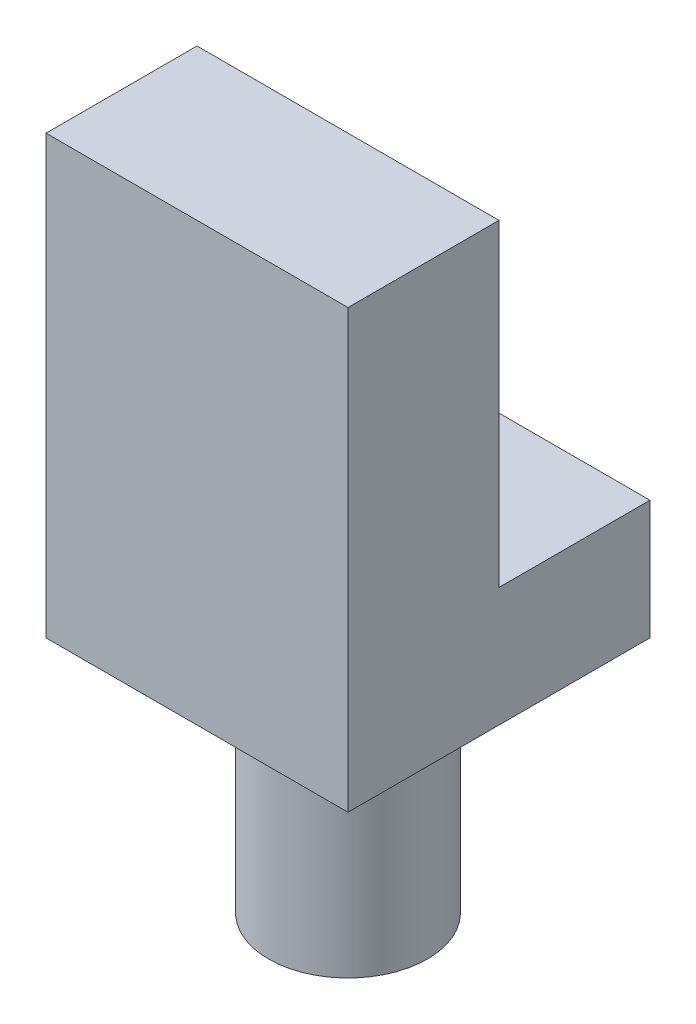
SolidWorks part; units mm, degrees
material "5086-H32, Rod (SS)"
ref_plane "Front Plane" through (0, 0, 0) normal (0, 0, 1) x (1, 0, 0)
ref_plane "Top Plane" through (0, 0, 0) normal (0, 1, 0) x (1, 0, 0)
ref_plane "Right Plane" through (0, 0, 0) normal (1, 0, 0) x (0, 0, -1)
sketch "Sketch1" plane through (0, 0, 0) normal (0, 1, 0) x (1, 0, 0)
  circle A0 centre (0, 0) radius 10
  dimension "D1" = 20
extrude "Boss-Extrude1" add sketch "Sketch1" along normal blind 30
sketch "Sketch2" plane through (0, 30, 0) normal (0, 1, 0) x (1, 0, 0)
  line L1 (-19, -19) -> (19, -19)
  line L2 (-19, -19) -> (-19, 19)
  line L3 (-19, 19) -> (19, 19)
  line L4 (19, -19) -> (19, 19)
  line L5 (-19, -19) -> (19, 19) construction
  line L6 (-19, 19) -> (19, -19) construction
  point P0 (0, 0)
  dimension "D1" = 38
extrude "Boss-Extrude2" add sketch "Sketch2" along normal blind 15
sketch "Sketch3" plane through (0, 45, 0) normal (0, 1, 0) x (1, 0, 0)
  line L0 (19, -19) -> (19, 19) construction
  line L1 (-19, -19) -> (19, -19)
  line L2 (-19, -19) -> (-19, 0)
  line L3 (-19, 0) -> (19, 0)
  line L4 (19, -19) -> (19, 0)
extrude "Boss-Extrude3" add sketch "Sketch3" along normal blind 40
sketch3d "3DSketch1"
  point P0 (19, 85, -29)
